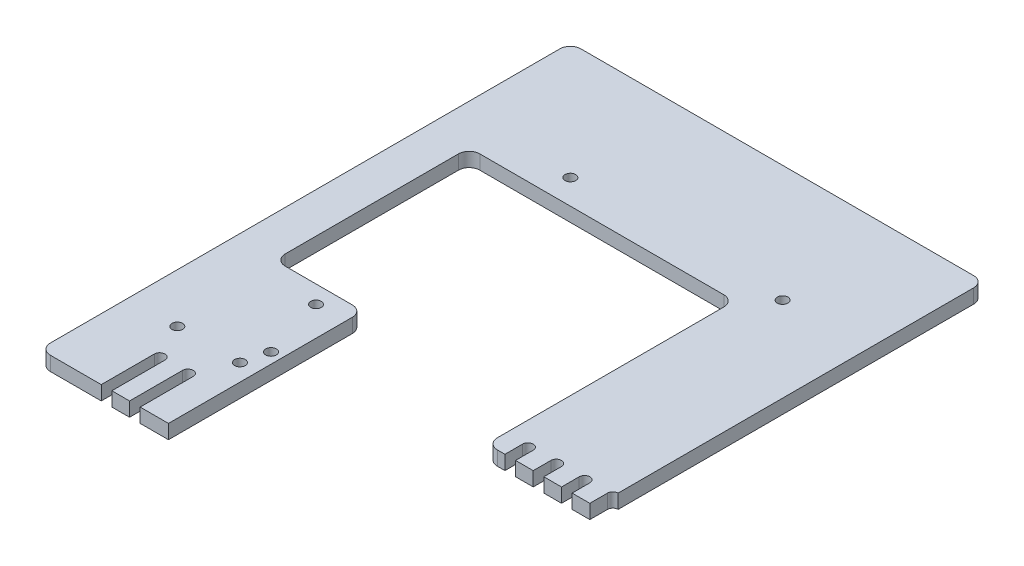
SolidWorks part; units mm, degrees
ref_plane "前视基准面" through (0, 0, 0) normal (0, 0, 1) x (1, 0, 0)
ref_plane "上视基准面" through (0, 0, 0) normal (0, 1, 0) x (1, 0, 0)
ref_plane "右视基准面" through (0, 0, 0) normal (1, 0, 0) x (0, 0, -1)
other "Configuration Table"
sketch "草图1" plane through (0, 0, 0) normal (0, 1, 0) x (1, 0, 0)
  line L5 (-51.0973, -171.2423) -> (-45.0973, -171.2423)
  line L6 (-45.0973, -171.2423) -> (-45.0973, -177.2423)
  line L7 (-45.0973, -177.2423) -> (-51.0973, -177.2423)
  line L8 (-80.0973, -171.2423) -> (-86.0973, -171.2423)
  line L12 (-86.0973, -171.2423) -> (-86.0973, -177.2423)
  line L13 (-86.0973, -177.2423) -> (-80.0973, -177.2423)
  line L14 (-80.0973, -113.2423) -> (-86.0973, -113.2423)
  line L37 (-88.3873, -92.2423) -> (105.4227, -92.2423) construction
  line L38 (105.4227, -92.2423) -> (105.4227, -192.2423) construction
  line L39 (105.4227, -192.2423) -> (-88.3873, -192.2423) construction
  line L40 (-88.3873, -192.2423) -> (-88.3873, -92.2423) construction
  line L42 (-105.0973, -197.2423) -> (122.1327, -197.2423)
  line L43 (122.1327, -197.2423) -> (122.1327, -87.2423)
  line L44 (122.1327, -87.2423) -> (-105.0973, -87.2423)
  line L46 (-105.0973, -87.2423) -> (-105.0973, -197.2423)
  line L48 (-80.0973, -87.2423) -> (-80.0973, -113.7423)
  line L49 (-80.0973, -113.7423) -> (-51.0973, -113.7423)
  line L50 (-51.0973, -113.7423) -> (-51.0973, -87.2423)
  line L52 (-80.0973, -197.2423) -> (-80.0973, -170.7423)
  line L53 (-80.0973, -170.7423) -> (-51.0973, -170.7423)
  line L54 (-51.0973, -170.7423) -> (-51.0973, -197.2423)
  line L56 (97.1327, -87.2423) -> (97.1327, -113.7423)
  line L57 (97.1327, -113.7423) -> (68.1327, -113.7423)
  line L58 (68.1327, -113.7423) -> (68.1327, -87.2423)
  line L60 (68.1327, -197.2423) -> (68.1327, -170.7423)
  line L61 (68.1327, -170.7423) -> (97.1327, -170.7423)
  line L62 (97.1327, -170.7423) -> (97.1327, -197.2423)
  line L63 (-86.0973, -113.2423) -> (-86.0973, -107.2423)
  line L64 (-86.0973, -107.2423) -> (-80.0973, -107.2423)
  line L66 (-51.0973, -107.2423) -> (-45.0973, -107.2423)
  line L67 (-45.0973, -107.2423) -> (-45.0973, -113.2423)
  line L68 (-45.0973, -113.2423) -> (-51.0973, -113.2423)
  line L70 (-86.0973, -110.2423) -> (-80.0973, -110.2423) construction
  line L72 (-83.0973, -107.2423) -> (-83.0973, -113.2423) construction
  line L73 (-51.0973, -110.2423) -> (-45.0973, -110.2423) construction
  line L74 (-48.0973, -107.2423) -> (-48.0973, -113.2423) construction
  line L75 (-86.0973, -174.2423) -> (-80.0973, -174.2423) construction
  line L76 (-83.0973, -171.2423) -> (-83.0973, -177.2423) construction
  line L77 (-48.0973, -171.2423) -> (-48.0973, -177.2423) construction
  line L78 (-45.0973, -174.2423) -> (-51.0973, -174.2423) construction
  line L79 (68.1327, -171.2423) -> (62.1327, -171.2423)
  line L80 (62.1327, -171.2423) -> (62.1327, -177.2423)
  line L81 (62.1327, -177.2423) -> (68.1327, -177.2423)
  line L82 (68.1327, -107.2423) -> (62.1327, -107.2423)
  line L83 (62.1327, -107.2423) -> (62.1327, -113.2423)
  line L84 (62.1327, -113.2423) -> (68.1327, -113.2423)
  line L85 (97.1327, -107.2423) -> (103.1327, -107.2423)
  line L86 (103.1327, -107.2423) -> (103.1327, -113.2423)
  line L87 (103.1327, -113.2423) -> (97.1327, -113.2423)
  line L88 (97.1327, -171.2423) -> (103.1327, -171.2423)
  line L89 (103.1327, -171.2423) -> (103.1327, -177.2423)
  line L90 (103.1327, -177.2423) -> (97.1327, -177.2423)
  line L91 (65.1327, -107.2423) -> (65.1327, -113.2423) construction
  line L92 (62.1327, -110.2423) -> (68.3912, -110.2423) construction
  line L93 (97.1327, -110.2423) -> (103.1327, -110.2423) construction
  line L94 (100.1327, -107.2423) -> (100.1327, -113.2423) construction
  line L95 (62.1327, -174.2423) -> (68.3912, -174.2423) construction
  line L96 (65.1327, -171.2423) -> (65.1327, -177.2423) construction
  line L97 (97.1327, -174.2423) -> (103.1327, -174.2423) construction
  line L98 (100.1327, -171.2423) -> (100.1327, -177.2423) construction
  line L99 (-105.0973, -142.2423) -> (122.1327, -142.2423) construction
  line L100 (8.5177, -87.2423) -> (8.5177, -197.2423) construction
  line L101 (8.5177, -97.2423) -> (8.5177, -137.2423) construction
  line L104 (10.0177, -97.2423) -> (10.0177, -137.2423)
  line L107 (7.0177, -97.2423) -> (7.0177, -137.2423)
  line L110 (8.5177, -147.2423) -> (8.5177, -187.2423) construction
  line L113 (10.0177, -147.2423) -> (10.0177, -187.2423)
  line L114 (7.0177, -147.2423) -> (7.0177, -187.2423)
  line L115 (16.5177, -97.2423) -> (16.5177, -137.2423) construction
  line L116 (18.0177, -97.2423) -> (18.0177, -137.2423)
  line L117 (15.0177, -97.2423) -> (15.0177, -137.2423)
  line L118 (16.5177, -147.2423) -> (16.5177, -187.2423) construction
  line L119 (18.0177, -147.2423) -> (18.0177, -187.2423)
  line L120 (15.0177, -147.2423) -> (15.0177, -187.2423)
  line L121 (24.5177, -97.2423) -> (24.5177, -137.2423) construction
  line L122 (26.0177, -97.2423) -> (26.0177, -137.2423)
  line L123 (23.0177, -97.2423) -> (23.0177, -137.2423)
  line L124 (24.5177, -147.2423) -> (24.5177, -187.2423) construction
  line L125 (26.0177, -147.2423) -> (26.0177, -187.2423)
  line L126 (23.0177, -147.2423) -> (23.0177, -187.2423)
  line L127 (32.5177, -97.2423) -> (32.5177, -137.2423) construction
  line L128 (34.0177, -97.2423) -> (34.0177, -137.2423)
  line L129 (31.0177, -97.2423) -> (31.0177, -137.2423)
  line L130 (40.5177, -97.2423) -> (40.5177, -137.2423) construction
  line L131 (42.0177, -97.2423) -> (42.0177, -137.2423)
  line L132 (39.0177, -97.2423) -> (39.0177, -137.2423)
  line L133 (32.5177, -147.2423) -> (32.5177, -187.2423) construction
  line L136 (40.5177, -147.2423) -> (40.5177, -187.2423) construction
  line L137 (42.0177, -147.2423) -> (42.0177, -187.2423)
  line L138 (39.0177, -147.2423) -> (39.0177, -187.2423)
  line L139 (34.0177, -147.2423) -> (34.0177, -187.2423)
  line L140 (31.0177, -147.2423) -> (31.0177, -187.2423)
  line L141 (0.5177, -97.2423) -> (0.5177, -137.2423) construction
  line L142 (2.0177, -97.2423) -> (2.0177, -137.2423)
  line L143 (-0.9823, -97.2423) -> (-0.9823, -137.2423)
  line L144 (-7.4823, -97.2423) -> (-7.4823, -137.2423) construction
  line L145 (-5.9823, -97.2423) -> (-5.9823, -137.2423)
  line L146 (-8.9823, -97.2423) -> (-8.9823, -137.2423)
  line L147 (-15.4823, -97.2423) -> (-15.4823, -137.2423) construction
  line L148 (-13.9823, -97.2423) -> (-13.9823, -137.2423)
  line L149 (-16.9823, -97.2423) -> (-16.9823, -137.2423)
  line L150 (-23.4823, -97.2423) -> (-23.4823, -137.2423) construction
  line L151 (-21.9823, -97.2423) -> (-21.9823, -137.2423)
  line L152 (-24.9823, -97.2423) -> (-24.9823, -137.2423)
  line L153 (0.5177, -147.2423) -> (0.5177, -187.2423) construction
  line L154 (2.0177, -147.2423) -> (2.0177, -187.2423)
  line L155 (-0.9823, -147.2423) -> (-0.9823, -187.2423)
  line L156 (-7.4823, -147.2423) -> (-7.4823, -187.2423) construction
  line L157 (-5.9823, -147.2423) -> (-5.9823, -187.2423)
  line L158 (-8.9823, -147.2423) -> (-8.9823, -187.2423)
  line L159 (-15.4823, -147.2423) -> (-15.4823, -187.2423) construction
  line L160 (-13.9823, -147.2423) -> (-13.9823, -187.2423)
  line L161 (-16.9823, -147.2423) -> (-16.9823, -187.2423)
  line L162 (-23.4823, -147.2423) -> (-23.4823, -187.2423) construction
  line L163 (-21.9823, -147.2423) -> (-21.9823, -187.2423)
  line L164 (-24.9823, -147.2423) -> (-24.9823, -187.2423)
  line L165 (-102.5973, -117.2423) -> (-102.5973, -167.2423) construction
  line L166 (-84.8973, -117.2423) -> (-84.8973, -167.2423) construction
  line L167 (119.6327, -117.2423) -> (119.6327, -167.2423) construction
  line L168 (119.6327, -167.2423) -> (101.9327, -167.2423) construction
  line L169 (101.9327, -167.2423) -> (101.9327, -117.2423) construction
  line L170 (101.9327, -117.2423) -> (119.6327, -117.2423) construction
  line L171 (-30.0973, -87.2423) -> (-30.0973, -102.2423)
  line L174 (-30.0973, -102.2423) -> (47.1327, -102.2423)
  line L177 (47.1327, -102.2423) -> (47.1327, -87.2423)
  line L180 (-30.0973, -197.2423) -> (-30.0973, -182.2423)
  line L183 (-57.5973, -147.2423) -> (-57.5973, -160.7423) construction
  line L186 (-56.0973, -147.2423) -> (-56.0973, -160.7423)
  line L189 (-59.0973, -147.2423) -> (-59.0973, -160.7423)
  line L190 (-97.5973, -127.2423) -> (-97.5973, -157.2423) construction
  line L191 (-96.0973, -127.2423) -> (-96.0973, -157.2423)
  line L192 (-99.0973, -127.2423) -> (-99.0973, -157.2423)
  line L193 (-89.5973, -127.2423) -> (-89.5973, -157.2423) construction
  line L194 (-88.0973, -127.2423) -> (-88.0973, -157.2423)
  line L195 (-91.0973, -127.2423) -> (-91.0973, -157.2423)
  line L196 (-65.5973, -147.2423) -> (-65.5973, -160.7423) construction
  line L197 (-64.0973, -147.2423) -> (-64.0973, -160.7423)
  line L198 (-67.0973, -147.2423) -> (-67.0973, -160.7423)
  line L199 (-73.5973, -147.2423) -> (-73.5973, -160.7423) construction
  line L200 (-72.0973, -147.2423) -> (-72.0973, -160.7423)
  line L201 (-75.0973, -147.2423) -> (-75.0973, -160.7423)
  line L202 (-73.5973, -137.2423) -> (-73.5973, -123.7423) construction
  line L203 (-75.0973, -137.2423) -> (-75.0973, -123.7423)
  line L204 (-72.0973, -137.2423) -> (-72.0973, -123.7423)
  line L205 (-65.5973, -137.2423) -> (-65.5973, -123.7423) construction
  line L206 (-67.0973, -137.2423) -> (-67.0973, -123.7423)
  line L207 (-64.0973, -137.2423) -> (-64.0973, -123.7423)
  line L208 (-57.5973, -137.2423) -> (-57.5973, -123.7423) construction
  line L209 (-59.0973, -137.2423) -> (-59.0973, -123.7423)
  line L210 (-56.0973, -137.2423) -> (-56.0973, -123.7423)
  line L211 (114.6327, -127.2423) -> (114.6327, -157.2423) construction
  line L212 (116.1327, -127.2423) -> (116.1327, -157.2423)
  line L213 (113.1327, -127.2423) -> (113.1327, -157.2423)
  line L214 (106.6327, -127.2423) -> (106.6327, -157.2423) construction
  line L215 (108.1327, -127.2423) -> (108.1327, -157.2423)
  line L216 (105.1327, -127.2423) -> (105.1327, -157.2423)
  line L217 (83.8086, -123.7423) -> (83.8086, -137.2423) construction
  line L218 (85.3086, -123.7423) -> (85.3086, -137.2423)
  line L219 (82.3086, -123.7423) -> (82.3086, -137.2423)
  line L220 (83.8086, -147.2423) -> (83.8086, -160.7423) construction
  line L221 (85.3086, -147.2423) -> (85.3086, -160.7423)
  line L222 (82.3086, -147.2423) -> (82.3086, -160.7423)
  line L223 (75.8086, -123.7423) -> (75.8086, -137.2423) construction
  line L224 (77.3086, -123.7423) -> (77.3086, -137.2423)
  line L225 (74.3086, -123.7423) -> (74.3086, -137.2423)
  line L226 (75.8086, -147.2423) -> (75.8086, -160.7423) construction
  line L227 (77.3086, -147.2423) -> (77.3086, -160.7423)
  line L228 (74.3086, -147.2423) -> (74.3086, -160.7423)
  line L229 (91.8086, -123.7423) -> (91.8086, -137.2423) construction
  line L230 (93.3086, -123.7423) -> (93.3086, -137.2423)
  line L231 (90.3086, -123.7423) -> (90.3086, -137.2423)
  line L232 (91.8086, -147.2423) -> (91.8086, -160.7423) construction
  line L233 (93.3086, -147.2423) -> (93.3086, -160.7423)
  line L234 (90.3086, -147.2423) -> (90.3086, -160.7423)
  line L235 (-141.4823, -142.2423) -> (158.5177, -142.2423) construction
  line L236 (-141.4823, 7.7577) -> (158.5177, 7.7577)
  line L237 (-141.4823, 7.7577) -> (-141.4823, -292.2423)
  line L238 (-141.4823, -292.2423) -> (158.5177, -292.2423)
  line L239 (158.5177, 7.7577) -> (158.5177, -292.2423)
  line L240 (-105.0973, -87.2423) -> (-105.0973, -32.2423) construction
  line L241 (-105.0973, -32.2423) -> (-30.0973, -32.2423) construction
  line L242 (-30.0973, -32.2423) -> (-30.0973, -87.2423) construction
  line L243 (-105.0973, -197.2423) -> (-105.0973, -252.2423) construction
  line L244 (-105.0973, -252.2423) -> (-30.0973, -252.2423) construction
  line L245 (-30.0973, -252.2423) -> (-30.0973, -197.2423) construction
  line L246 (122.1327, -87.2423) -> (122.1327, -32.2423) construction
  line L247 (122.1327, -32.2423) -> (47.1327, -32.2423) construction
  line L248 (47.1327, -32.2423) -> (47.1327, -87.2423) construction
  line L249 (122.1327, -197.2423) -> (122.1327, -252.2423) construction
  line L250 (122.1327, -252.2423) -> (47.1327, -252.2423) construction
  line L251 (47.1327, -252.2423) -> (47.1327, -197.2423) construction
  line L252 (-105.0973, -87.2423) -> (-105.0973, -32.2423)
  line L253 (-105.0973, -32.2423) -> (-30.0973, -32.2423)
  line L254 (-30.0973, -32.2423) -> (-30.0973, -87.2423)
  line L255 (47.1327, -87.2423) -> (47.1327, -32.2423)
  line L256 (47.1327, -32.2423) -> (122.1327, -32.2423)
  line L257 (122.1327, -32.2423) -> (122.1327, -87.2423)
  line L258 (-105.0973, -197.2423) -> (-105.0973, -252.2423)
  line L259 (-105.0973, -252.2423) -> (-30.0973, -252.2423)
  line L260 (-30.0973, -252.2423) -> (-30.0973, -197.2423)
  line L261 (47.1327, -197.2423) -> (47.1327, -252.2423)
  line L262 (47.1327, -252.2423) -> (122.1327, -252.2423)
  line L263 (122.1327, -252.2423) -> (122.1327, -197.2423)
  line L264 (-80.0973, -113.7423) -> (-80.0973, -171.2423)
  line L265 (97.1327, -113.7423) -> (97.1327, -170.7423)
  line L266 (-30.0973, -182.2423) -> (47.1327, -182.2423)
  line L267 (47.1327, -182.2423) -> (47.1327, -197.2423)
  line L268 (-141.4823, -142.2423) -> (158.5177, -142.2423)
  line L269 (-116.4823, 7.7577) -> (-116.4823, -292.2423)
  line L270 (158.5177, 7.7577) -> (183.5177, 7.7577)
  line L271 (183.5177, 7.7577) -> (183.5177, -292.2423)
  line L272 (183.5177, -292.2423) -> (158.5177, -292.2423)
  line L273 (158.5177, -142.2423) -> (183.5177, -142.2423)
  line L274 (143.5177, -89.7423) -> (143.5177, -194.7423) construction
  line L275 (143.5177, -89.7423) -> (143.5177, -79.2423) construction
  line L276 (143.5177, -89.7423) -> (154.0177, -89.7423) construction
  line L277 (143.5177, -194.7423) -> (143.5177, -205.2423) construction
  line L278 (143.5177, -194.7423) -> (154.0177, -194.7423) construction
  line L279 (0.5177, 7.7577) -> (0.5177, -95.7423)
  circle A9 centre (-88.3873, -92.2423) radius 1.5
  circle A10 centre (105.4227, -92.2423) radius 1.5
  circle A11 centre (105.4227, -192.2423) radius 1.5
  circle A12 centre (-88.3873, -192.2423) radius 1.5
  circle A13 centre (-37.0973, -92.2423) radius 1.5
  circle A14 centre (-37.0973, -192.2423) radius 1.5
  circle A15 centre (54.1327, -192.2423) radius 1.5
  circle A16 centre (54.1327, -92.2423) radius 1.5
  circle A17 centre (-83.0973, -110.2423) radius 1.5
  circle A18 centre (-48.0973, -110.2423) radius 1.5
  circle A19 centre (-83.0973, -174.2423) radius 1.5
  circle A20 centre (-48.0973, -174.2423) radius 1.5
  circle A21 centre (65.1327, -110.2423) radius 1.5
  circle A22 centre (100.1327, -110.2423) radius 1.5
  circle A23 centre (65.2619, -174.2423) radius 1.5
  circle A24 centre (100.1327, -174.2423) radius 1.5
  arc A33 (10.0177, -97.2423) -> (7.0177, -97.2423) centre (8.5177, -97.2423) ccw
  arc A34 (7.0177, -137.2423) -> (10.0177, -137.2423) centre (8.5177, -137.2423) ccw
  arc A35 (10.0177, -147.2423) -> (7.0177, -147.2423) centre (8.5177, -147.2423) ccw
  arc A36 (7.0177, -187.2423) -> (10.0177, -187.2423) centre (8.5177, -187.2423) ccw
  arc A37 (18.0177, -97.2423) -> (15.0177, -97.2423) centre (16.5177, -97.2423) ccw
  arc A38 (15.0177, -137.2423) -> (18.0177, -137.2423) centre (16.5177, -137.2423) ccw
  arc A39 (18.0177, -147.2423) -> (15.0177, -147.2423) centre (16.5177, -147.2423) ccw
  arc A40 (15.0177, -187.2423) -> (18.0177, -187.2423) centre (16.5177, -187.2423) ccw
  arc A41 (26.0177, -97.2423) -> (23.0177, -97.2423) centre (24.5177, -97.2423) ccw
  arc A42 (23.0177, -137.2423) -> (26.0177, -137.2423) centre (24.5177, -137.2423) ccw
  arc A43 (26.0177, -147.2423) -> (23.0177, -147.2423) centre (24.5177, -147.2423) ccw
  arc A44 (23.0177, -187.2423) -> (26.0177, -187.2423) centre (24.5177, -187.2423) ccw
  arc A45 (34.0177, -97.2423) -> (31.0177, -97.2423) centre (32.5177, -97.2423) ccw
  arc A46 (31.0177, -137.2423) -> (34.0177, -137.2423) centre (32.5177, -137.2423) ccw
  arc A47 (42.0177, -97.2423) -> (39.0177, -97.2423) centre (40.5177, -97.2423) ccw
  arc A48 (39.0177, -137.2423) -> (42.0177, -137.2423) centre (40.5177, -137.2423) ccw
  arc A51 (42.0177, -147.2423) -> (39.0177, -147.2423) centre (40.5177, -147.2423) ccw
  arc A52 (39.0177, -187.2423) -> (42.0177, -187.2423) centre (40.5177, -187.2423) ccw
  arc A53 (34.0177, -147.2423) -> (31.0177, -147.2423) centre (32.5177, -147.2423) ccw
  arc A54 (31.0177, -187.2423) -> (34.0177, -187.2423) centre (32.5177, -187.2423) ccw
  arc A55 (2.0177, -97.2423) -> (-0.9823, -97.2423) centre (0.5177, -97.2423) ccw
  arc A56 (-0.9823, -137.2423) -> (2.0177, -137.2423) centre (0.5177, -137.2423) ccw
  arc A57 (-5.9823, -97.2423) -> (-8.9823, -97.2423) centre (-7.4823, -97.2423) ccw
  arc A58 (-8.9823, -137.2423) -> (-5.9823, -137.2423) centre (-7.4823, -137.2423) ccw
  arc A59 (-13.9823, -97.2423) -> (-16.9823, -97.2423) centre (-15.4823, -97.2423) ccw
  arc A60 (-16.9823, -137.2423) -> (-13.9823, -137.2423) centre (-15.4823, -137.2423) ccw
  arc A61 (-21.9823, -97.2423) -> (-24.9823, -97.2423) centre (-23.4823, -97.2423) ccw
  arc A62 (-24.9823, -137.2423) -> (-21.9823, -137.2423) centre (-23.4823, -137.2423) ccw
  arc A63 (2.0177, -147.2423) -> (-0.9823, -147.2423) centre (0.5177, -147.2423) ccw
  arc A64 (-0.9823, -187.2423) -> (2.0177, -187.2423) centre (0.5177, -187.2423) ccw
  arc A65 (-5.9823, -147.2423) -> (-8.9823, -147.2423) centre (-7.4823, -147.2423) ccw
  arc A66 (-8.9823, -187.2423) -> (-5.9823, -187.2423) centre (-7.4823, -187.2423) ccw
  arc A67 (-13.9823, -147.2423) -> (-16.9823, -147.2423) centre (-15.4823, -147.2423) ccw
  arc A68 (-16.9823, -187.2423) -> (-13.9823, -187.2423) centre (-15.4823, -187.2423) ccw
  arc A69 (-21.9823, -147.2423) -> (-24.9823, -147.2423) centre (-23.4823, -147.2423) ccw
  arc A70 (-24.9823, -187.2423) -> (-21.9823, -187.2423) centre (-23.4823, -187.2423) ccw
  circle A71 centre (-102.5973, -117.2423) radius 1.5
  circle A72 centre (-102.5973, -167.2423) radius 1.5
  circle A73 centre (-84.8973, -117.2423) radius 1.5
  circle A74 centre (-84.8973, -167.2423) radius 1.5
  circle A75 centre (119.6327, -117.2423) radius 1.5
  circle A76 centre (119.6327, -167.2423) radius 1.5
  circle A78 centre (101.9327, -117.2423) radius 1.5
  circle A79 centre (101.9327, -167.2423) radius 1.5
  arc A98 (-56.0973, -147.2423) -> (-59.0973, -147.2423) centre (-57.5973, -147.2423) ccw
  arc A99 (-59.0973, -160.7423) -> (-56.0973, -160.7423) centre (-57.5973, -160.7423) ccw
  arc A100 (-96.0973, -127.2423) -> (-99.0973, -127.2423) centre (-97.5973, -127.2423) ccw
  arc A101 (-99.0973, -157.2423) -> (-96.0973, -157.2423) centre (-97.5973, -157.2423) ccw
  arc A102 (-88.0973, -127.2423) -> (-91.0973, -127.2423) centre (-89.5973, -127.2423) ccw
  arc A103 (-91.0973, -157.2423) -> (-88.0973, -157.2423) centre (-89.5973, -157.2423) ccw
  arc A104 (-64.0973, -147.2423) -> (-67.0973, -147.2423) centre (-65.5973, -147.2423) ccw
  arc A105 (-67.0973, -160.7423) -> (-64.0973, -160.7423) centre (-65.5973, -160.7423) ccw
  arc A106 (-72.0973, -147.2423) -> (-75.0973, -147.2423) centre (-73.5973, -147.2423) ccw
  arc A107 (-75.0973, -160.7423) -> (-72.0973, -160.7423) centre (-73.5973, -160.7423) ccw
  arc A108 (-75.0973, -137.2423) -> (-72.0973, -137.2423) centre (-73.5973, -137.2423) ccw
  arc A109 (-72.0973, -123.7423) -> (-75.0973, -123.7423) centre (-73.5973, -123.7423) ccw
  arc A110 (-67.0973, -137.2423) -> (-64.0973, -137.2423) centre (-65.5973, -137.2423) ccw
  arc A111 (-64.0973, -123.7423) -> (-67.0973, -123.7423) centre (-65.5973, -123.7423) ccw
  arc A112 (-59.0973, -137.2423) -> (-56.0973, -137.2423) centre (-57.5973, -137.2423) ccw
  arc A113 (-56.0973, -123.7423) -> (-59.0973, -123.7423) centre (-57.5973, -123.7423) ccw
  arc A114 (116.1327, -127.2423) -> (113.1327, -127.2423) centre (114.6327, -127.2423) ccw
  arc A115 (113.1327, -157.2423) -> (116.1327, -157.2423) centre (114.6327, -157.2423) ccw
  arc A116 (108.1327, -127.2423) -> (105.1327, -127.2423) centre (106.6327, -127.2423) ccw
  arc A117 (105.1327, -157.2423) -> (108.1327, -157.2423) centre (106.6327, -157.2423) ccw
  arc A118 (85.3086, -123.7423) -> (82.3086, -123.7423) centre (83.8086, -123.7423) ccw
  arc A119 (82.3086, -137.2423) -> (85.3086, -137.2423) centre (83.8086, -137.2423) ccw
  arc A120 (85.3086, -147.2423) -> (82.3086, -147.2423) centre (83.8086, -147.2423) ccw
  arc A121 (82.3086, -160.7423) -> (85.3086, -160.7423) centre (83.8086, -160.7423) ccw
  arc A122 (77.3086, -123.7423) -> (74.3086, -123.7423) centre (75.8086, -123.7423) ccw
  arc A123 (74.3086, -137.2423) -> (77.3086, -137.2423) centre (75.8086, -137.2423) ccw
  arc A124 (77.3086, -147.2423) -> (74.3086, -147.2423) centre (75.8086, -147.2423) ccw
  arc A125 (74.3086, -160.7423) -> (77.3086, -160.7423) centre (75.8086, -160.7423) ccw
  arc A126 (93.3086, -123.7423) -> (90.3086, -123.7423) centre (91.8086, -123.7423) ccw
  arc A127 (90.3086, -137.2423) -> (93.3086, -137.2423) centre (91.8086, -137.2423) ccw
  arc A128 (93.3086, -147.2423) -> (90.3086, -147.2423) centre (91.8086, -147.2423) ccw
  arc A129 (90.3086, -160.7423) -> (93.3086, -160.7423) centre (91.8086, -160.7423) ccw
  circle A130 centre (-23.4823, -97.2423) radius 1.5
  circle A131 centre (40.5177, -97.2423) radius 1.5
  circle A132 centre (-7.4823, -97.2423) radius 1.5
  circle A133 centre (24.5177, -97.2423) radius 1.5
  circle A134 centre (-23.4823, -187.2423) radius 1.5
  circle A135 centre (-7.4823, -187.2423) radius 1.5
  circle A136 centre (24.5177, -187.2423) radius 1.5
  circle A137 centre (40.5177, -187.2423) radius 1.5
  circle A138 centre (143.5177, -89.7423) radius 10.5 construction
  circle A139 centre (143.5177, -194.7423) radius 10.5 construction
  circle A140 centre (143.5177, -205.2423) radius 1.5
  circle A141 centre (154.0177, -194.7423) radius 1.5
  circle A142 centre (143.5177, -184.2423) radius 1.5
  circle A143 centre (143.5177, -79.2423) radius 1.5
  circle A144 centre (154.0177, -89.7423) radius 1.5
  circle A145 centre (143.5177, -100.2423) radius 1.5
  circle A146 centre (-23.4823, -25.2423) radius 1.5
  circle A147 centre (-83.4823, -25.2423) radius 1.5
  circle A148 centre (105.1327, -23.2423) radius 1.5
  circle A149 centre (41.1327, -39.2423) radius 1.5
  circle A150 centre (64.1327, -23.2423) radius 1.5
  circle A151 centre (41.1327, -79.2423) radius 1.5
  point P13 (-45.0973, -110.2423)
  point P124 (8.5177, -117.2423)
  point P129 (8.5177, -167.2423)
  point P138 (16.5177, -117.2423)
  point P143 (16.5177, -167.2423)
  point P150 (24.5177, -117.2423)
  point P157 (24.5177, -167.2423)
  point P166 (32.5177, -117.2423)
  point P171 (40.5177, -117.2423)
  point P180 (32.5177, -167.2423)
  point P186 (40.5177, -167.2423)
  point P191 (0.5177, -117.2423)
  point P198 (-7.4823, -117.2423)
  point P205 (-15.4823, -117.2423)
  point P212 (-23.4823, -117.2423)
  point P221 (0.5177, -167.2423)
  point P226 (-7.4823, -167.2423)
  point P233 (-15.4823, -167.2423)
  point P240 (-23.4823, -167.2423)
  point P265 (-31.4823, -117.2423)
  point P270 (-31.4823, -167.2423)
  point P277 (48.5177, -117.2423)
  point P284 (48.5177, -167.2423)
  point P293 (-57.5973, -153.9923)
  point P300 (-97.5973, -142.2423)
  point P307 (-89.5973, -142.2423)
  point P314 (-65.5973, -153.9923)
  point P319 (-73.5973, -153.9923)
  point P326 (-73.5973, -130.4923)
  point P333 (-65.5973, -130.4923)
  point P340 (-57.5973, -130.4923)
  point P347 (114.6327, -142.2423)
  point P354 (106.6327, -142.2423)
  point P363 (83.8086, -130.4923)
  point P368 (83.8086, -153.9923)
  point P375 (75.8086, -130.4923)
  point P382 (75.8086, -153.9923)
  point P389 (91.8086, -130.4923)
  point P396 (91.8086, -153.9923)
  dimension "D23" = 3
  dimension "D24" = 3
  dimension "D27" = 5
  dimension "D30" = 3
  dimension "D35" = 3
  dimension "D11" = 3
  dimension "D13" = 3
  dimension "D16" = 6
  dimension "D36" = 3
  dimension "D38" = 3
  dimension "D39" = 3
  dimension "D51" = 3
  dimension "D54" = 3
  dimension "D56" = 3
  dimension "D58" = 3
  dimension "D12" = 3
  dimension "D14" = 3
  dimension "D20" = 3
  dimension "D21" = 3
  dimension "D22" = 3
  dimension "D80" = 3
  dimension "D81" = 3
  dimension "D84" = 3
  dimension "D85" = 3
  dimension "D88" = 3
  dimension "D89" = 3
  dimension "D90" = 3
  dimension "D91" = 3
  dimension "D153" = 3
  dimension "D154" = 3
  dimension "D155" = 3
  dimension "D156" = 3
  dimension "D157" = 3
  dimension "D158" = 3
  dimension "D159" = 3
  dimension "D160" = 3
  dimension "D162" = 3
  dimension "D163" = 3
  dimension "D164" = 3
  dimension "D165" = 3
  dimension "D166" = 3
  dimension "D167" = 3
  dimension "D168" = 21
  dimension "D169" = 21
  dimension "D173" = 3
  dimension "D174" = 3
  dimension "D176" = 3
  dimension "D179" = 3
  dimension "D181" = 3
  dimension "D183" = 3
  dimension "D1" = 20
  dimension "D2" = 6
  dimension "D6" = 6
  dimension "D7" = 6
  dimension "D8" = 20
  dimension "D9" = 6
  dimension "D10" = 6
  dimension "D15" = 6
  dimension "D17" = 6
  dimension "D18" = 6
  dimension "D19" = 6
  dimension "D25" = 5
  dimension "D26" = 3
  dimension "D28" = 10
  dimension "D29" = 10
  dimension "D31" = 193.81
  dimension "D32" = 3
  dimension "D33" = 3
  dimension "D34" = 3
  dimension "D37" = 8
  dimension "D40" = 110
  dimension "D41" = 5
  dimension "D42" = 5
  dimension "D43" = 16.71
  dimension "D44" = 16.71
  dimension "D45" = 25
  dimension "D46" = 29
  dimension "D47" = 26.5
  dimension "D48" = 26.5
  dimension "D49" = 29
  dimension "D50" = 25
  dimension "D52" = 14
  dimension "D53" = 8
  dimension "D55" = 14
  dimension "D57" = 14
  dimension "D59" = 14
  dimension "D60" = 3
  dimension "D61" = 3
  dimension "D62" = 3
  dimension "D63" = 3
  dimension "D64" = 8
  dimension "D65" = 8
  dimension "D66" = 3
  dimension "D67" = 3
  dimension "D68" = 3
  dimension "D69" = 3
  dimension "D70" = 8
  dimension "D71" = 8
  dimension "D72" = 8
  dimension "D73" = 8
  dimension "D74" = 3
  dimension "D75" = 3
  dimension "D76" = 3
  dimension "D77" = 3
  dimension "D78" = 25
  dimension "D79" = 25
  dimension "D82" = 2.5
  dimension "D83" = 17.7
  dimension "D86" = 17.7
  dimension "D87" = 2.5
  dimension "D92" = 25
  dimension "D93" = 25
  dimension "D94" = 10
  dimension "D95" = 5
  dimension "D96" = 15
  dimension "D97" = 15
  dimension "D98" = 14.5
  dimension "D99" = 25
  dimension "D100" = 3
  dimension "D101" = 3
  dimension "D102" = 25
  dimension "D103" = 52.5
  dimension "D104" = 7.5
  dimension "D105" = 15
  dimension "D106" = 15
  dimension "D107" = 3
  dimension "D108" = 8
  dimension "D109" = 3
  dimension "D110" = 3
  dimension "D111" = 3
  dimension "D112" = 3
  dimension "D113" = 3
  dimension "D114" = 10
  dimension "D115" = 5
  dimension "D116" = 8
  dimension "D117" = 8
  dimension "D118" = 8
  dimension "D119" = 3
  dimension "D120" = 3
  dimension "D121" = 7.5
  dimension "D122" = 8
  dimension "D123" = 15
  dimension "D124" = 15
  dimension "D125" = 15
  dimension "D126" = 15
  dimension "D127" = 3
  dimension "D128" = 3
  dimension "D129" = 3
  dimension "D130" = 3
  dimension "D131" = 3
  dimension "D132" = 3
  dimension "D133" = 5
  dimension "D134" = 10
  dimension "D135" = 5
  dimension "D136" = 10
  dimension "D137" = 8
  dimension "D138" = 8
  dimension "D139" = 300
  dimension "D140" = 300
  dimension "D141" = 227.23
  dimension "D142" = 36.385
  dimension "D143" = 36.385
  dimension "D144" = 95
  dimension "D145" = 55
  dimension "D146" = 75
  dimension "D147" = 75
  dimension "D148" = 55
  dimension "D149" = 75
  dimension "D150" = 55
  dimension "D151" = 75
  dimension "D152" = 55
  dimension "D161" = 52.5
  dimension "D170" = 40
  dimension "D171" = 72
  dimension "D172" = 60
  dimension "D175" = 78.385
  dimension "D177" = 31
  dimension "D178" = 47
  dimension "D180" = 142.385
  dimension "D182" = 119.385
  dimension "D184" = 87
  dimension "D185" = 6
extrude "凸台-拉伸1" add sketch "草图1" along normal blind 4 contours L279 L236 L269 L268 L46 L252 L253 L254 L44 A147 A146 | A61 L151 L174 L149 A59 L148 L146 A57 L145 L143 A55 L279 L44 L171 L152 | A102 L194 L268 L264 L48 L14 L63 L64 L44 L46 L192 A100 L191 L195 A73 A71 A9 | L64 L63 L14 L48 A17
fillet "圆角1" radius 3 8 edges at (-116.4823, 2, 142.2423) (-30.0973, 2, 32.2423) (-105.0973, 2, 32.2423) (-105.0973, 2, 87.2423) (-80.0973, 2, 87.2423) (-116.4823, 2, -7.7577) (0.5177, 2, -7.7577) (-30.0973, 2, 102.2423)
